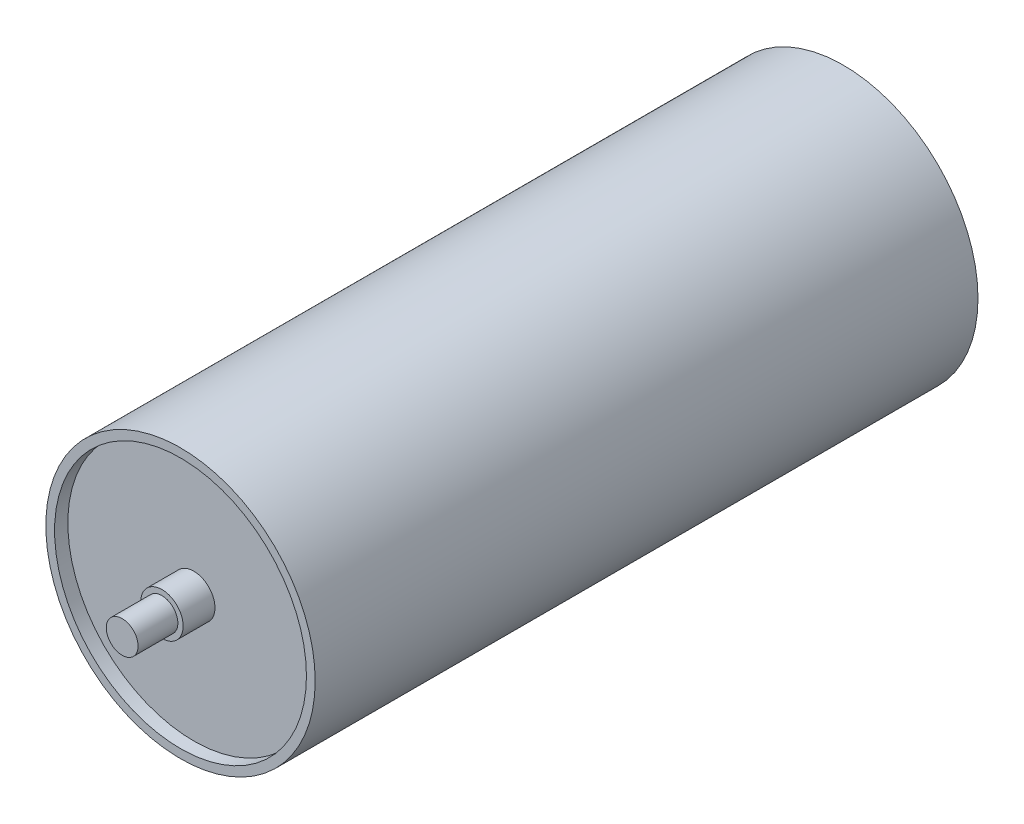
SolidWorks part; units mm, degrees
material "AISI 1010 Steel, hot rolled bar"
ref_plane "Front Plane" through (0, 0, 0) normal (0, 0, 1) x (1, 0, 0)
ref_plane "Top Plane" through (0, 0, 0) normal (0, 1, 0) x (1, 0, 0)
ref_plane "Right Plane" through (0, 0, 0) normal (1, 0, 0) x (0, 0, -1)
sketch "Sketch1" plane through (0, 0, 0) normal (0, 0, 1) x (1, 0, 0)
  circle A0 centre (0, 0) radius 50.8
  dimension "D1" = 101.6
extrude "Boss-Extrude1" add sketch "Sketch1" along normal blind 250
sketch "Sketch2" plane through (0, 0, 250) normal (0, 0, 1) x (1, 0, 0)
  circle A0 centre (0, 0) radius 47.5
  dimension "D1" = 95
extrude "Cut-Extrude1" cut sketch "Sketch2" against normal blind 5
sketch "Sketch3" plane through (0, 0, 0) normal (0, 0, -1) x (-1, 0, 0)
  circle A0 centre (0, 0) radius 47.5
  dimension "D1" = 95
extrude "Cut-Extrude2" cut sketch "Sketch3" against normal blind 5
sketch "Sketch4" plane through (0, 0, 5) normal (0, 0, -1) x (-1, 0, 0)
  circle A0 centre (0, 0) radius 8
extrude "Boss-Extrude2" add sketch "Sketch4" along normal blind 11
sketch "Sketch5" plane through (0, 0, 245) normal (0, 0, 1) x (1, 0, 0)
  circle A0 centre (0, 0) radius 8
extrude "Boss-Extrude3" add sketch "Sketch5" along normal blind 12
sketch "Sketch7" plane through (0, 0, -6) normal (0, 0, -1) x (-1, 0, 0)
  circle A0 centre (0, 0) radius 6
extrude "Boss-Extrude4" add sketch "Sketch7" along normal blind 10
sketch "Sketch8" plane through (0, 0, 257) normal (0, 0, 1) x (1, 0, 0)
  circle A0 centre (0, 0) radius 6
extrude "Boss-Extrude5" add sketch "Sketch8" along normal blind 15
